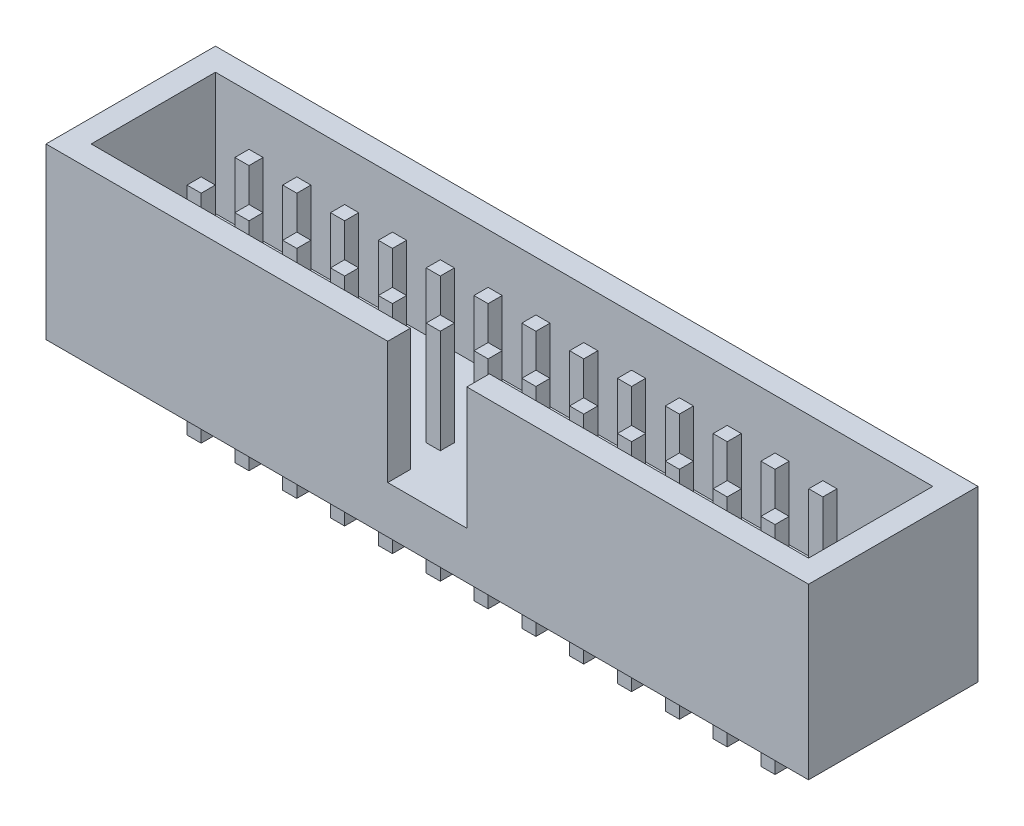
SolidWorks part; units mm, degrees
ref_plane "前视基准面" through (0, 0, 0) normal (0, 0, 1) x (1, 0, 0)
ref_plane "上视基准面" through (0, 0, 0) normal (0, 1, 0) x (1, 0, 0)
ref_plane "右视基准面" through (0, 0, 0) normal (1, 0, 0) x (0, 0, -1)
sketch "草图1" plane through (0, 0, 0) normal (0, 1, 0) x (1, 0, 0)
  line L0 (0, 85.0964) -> (0, -118.2031) construction
  line L1 (-20.25, 4.5) -> (20.25, 4.5)
  line L2 (-20.25, 4.5) -> (-20.25, -4.5)
  line L3 (-20.25, -4.5) -> (20.25, -4.5)
  line L4 (20.25, 4.5) -> (20.25, -4.5)
  line L5 (-200.5452, 0) -> (261.2352, 0) construction
  dimension "D1" = 9
  dimension "D2" = 40.5
extrude "拉伸1" add sketch "草图1" along normal blind 9
sketch "草图2" plane through (0, 9, 0) normal (0, 1, 0) x (-1, 0, 0)
  line L8 (-19.05, 3.3) -> (-19.05, -3.3)
  line L9 (19.05, 3.3) -> (-19.05, 3.3)
  line L10 (19.05, -3.3) -> (19.05, 3.3)
  line L11 (-19.05, -3.3) -> (19.05, -3.3)
  line L12 (-19.05, 3.3) -> (-19.05, -3.3)
  line L13 (19.05, 3.3) -> (-19.05, 3.3)
  line L14 (19.05, -3.3) -> (19.05, 3.3)
  line L15 (-19.05, -3.3) -> (19.05, -3.3)
  dimension "D1" = 1.2
extrude "切除-拉伸1" cut sketch "草图2" against normal blind 6.5
sketch "草图3" plane through (0, 0, 4.5) normal (0, 0, 1) x (1, 0, 0)
  line L0 (-20.25, 9) -> (20.25, 9) construction
  line L1 (-2.1, 9) -> (2.1, 9)
  line L2 (-2.1, 9) -> (-2.1, 2.5)
  line L3 (-2.1, 2.5) -> (2.1, 2.5)
  line L4 (2.1, 9) -> (2.1, 2.5)
  line L5 (-19.05, 2.5) -> (19.05, 2.5) construction
  line L6 (0, 9.4226) -> (0, -4.0288) construction
  dimension "D1" = 4.2
extrude "切除-拉伸2" cut sketch "草图3" against normal blind 6.5
sketch "草图5" plane through (0, 0, 0) normal (0, -1, 0) x (1, 0, 0)
  line L0 (0, 6.0683) -> (0, -6.9786) construction
  line L1 (-21.1981, 0) -> (21.4095, 0) construction
  line L2 (-2.4898, 1.27) -> (1.0953, 1.27) construction
  line L3 (-0.375, 0.895) -> (0.375, 0.895)
  line L4 (-0.375, 0.895) -> (-0.375, 1.645)
  line L5 (-0.375, 1.645) -> (0.375, 1.645)
  line L6 (0.375, 0.895) -> (0.375, 1.645)
  line L7 (2.165, 0.895) -> (2.915, 0.895)
  line L8 (2.165, 0.895) -> (2.165, 1.645)
  line L9 (2.165, 1.645) -> (2.915, 1.645)
  line L10 (2.915, 0.895) -> (2.915, 1.645)
  line L11 (4.705, 0.895) -> (5.455, 0.895)
  line L12 (4.705, 0.895) -> (4.705, 1.645)
  line L13 (4.705, 1.645) -> (5.455, 1.645)
  line L14 (5.455, 0.895) -> (5.455, 1.645)
  line L15 (7.245, 0.895) -> (7.995, 0.895)
  line L16 (7.245, 0.895) -> (7.245, 1.645)
  line L17 (7.245, 1.645) -> (7.995, 1.645)
  line L18 (7.995, 0.895) -> (7.995, 1.645)
  line L19 (9.785, 0.895) -> (10.535, 0.895)
  line L20 (9.785, 0.895) -> (9.785, 1.645)
  line L21 (9.785, 1.645) -> (10.535, 1.645)
  line L22 (10.535, 0.895) -> (10.535, 1.645)
  line L23 (12.325, 0.895) -> (13.075, 0.895)
  line L24 (12.325, 0.895) -> (12.325, 1.645)
  line L25 (12.325, 1.645) -> (13.075, 1.645)
  line L26 (13.075, 0.895) -> (13.075, 1.645)
  line L27 (14.865, 0.895) -> (15.615, 0.895)
  line L28 (14.865, 0.895) -> (14.865, 1.645)
  line L29 (14.865, 1.645) -> (15.615, 1.645)
  line L30 (15.615, 0.895) -> (15.615, 1.645)
  line L31 (-2.915, 0.895) -> (-2.165, 0.895)
  line L32 (-2.915, 0.895) -> (-2.915, 1.645)
  line L33 (-2.915, 1.645) -> (-2.165, 1.645)
  line L34 (-2.165, 0.895) -> (-2.165, 1.645)
  line L35 (-5.455, 0.895) -> (-4.705, 0.895)
  line L36 (-5.455, 0.895) -> (-5.455, 1.645)
  line L37 (-5.455, 1.645) -> (-4.705, 1.645)
  line L38 (-4.705, 0.895) -> (-4.705, 1.645)
  line L39 (-7.995, 0.895) -> (-7.245, 0.895)
  line L40 (-7.995, 0.895) -> (-7.995, 1.645)
  line L41 (-7.995, 1.645) -> (-7.245, 1.645)
  line L42 (-7.245, 0.895) -> (-7.245, 1.645)
  line L43 (-10.535, 0.895) -> (-9.785, 0.895)
  line L44 (-10.535, 0.895) -> (-10.535, 1.645)
  line L45 (-10.535, 1.645) -> (-9.785, 1.645)
  line L46 (-9.785, 0.895) -> (-9.785, 1.645)
  line L47 (-13.075, 0.895) -> (-12.325, 0.895)
  line L48 (-13.075, 0.895) -> (-13.075, 1.645)
  line L49 (-13.075, 1.645) -> (-12.325, 1.645)
  line L50 (-12.325, 0.895) -> (-12.325, 1.645)
  line L51 (-15.615, 0.895) -> (-14.865, 0.895)
  line L52 (-15.615, 0.895) -> (-15.615, 1.645)
  line L53 (-15.615, 1.645) -> (-14.865, 1.645)
  line L54 (-14.865, 0.895) -> (-14.865, 1.645)
  line L55 (-2.4898, -1.27) -> (1.0953, -1.27) construction
  line L56 (-14.865, -0.895) -> (-14.865, -1.645)
  line L57 (-15.615, -1.645) -> (-14.865, -1.645)
  line L58 (-15.615, -0.895) -> (-15.615, -1.645)
  line L59 (-15.615, -0.895) -> (-14.865, -0.895)
  line L60 (-12.325, -0.895) -> (-12.325, -1.645)
  line L61 (-13.075, -1.645) -> (-12.325, -1.645)
  line L62 (-13.075, -0.895) -> (-13.075, -1.645)
  line L63 (-13.075, -0.895) -> (-12.325, -0.895)
  line L64 (-9.785, -0.895) -> (-9.785, -1.645)
  line L65 (-10.535, -1.645) -> (-9.785, -1.645)
  line L66 (-10.535, -0.895) -> (-10.535, -1.645)
  line L67 (-10.535, -0.895) -> (-9.785, -0.895)
  line L68 (-7.245, -0.895) -> (-7.245, -1.645)
  line L69 (-7.995, -1.645) -> (-7.245, -1.645)
  line L70 (-7.995, -0.895) -> (-7.995, -1.645)
  line L71 (-7.995, -0.895) -> (-7.245, -0.895)
  line L72 (-4.705, -0.895) -> (-4.705, -1.645)
  line L73 (-5.455, -1.645) -> (-4.705, -1.645)
  line L74 (-5.455, -0.895) -> (-5.455, -1.645)
  line L75 (-5.455, -0.895) -> (-4.705, -0.895)
  line L76 (-2.165, -0.895) -> (-2.165, -1.645)
  line L77 (-2.915, -1.645) -> (-2.165, -1.645)
  line L78 (-2.915, -0.895) -> (-2.915, -1.645)
  line L79 (-2.915, -0.895) -> (-2.165, -0.895)
  line L80 (15.615, -0.895) -> (15.615, -1.645)
  line L81 (14.865, -1.645) -> (15.615, -1.645)
  line L82 (14.865, -0.895) -> (14.865, -1.645)
  line L83 (14.865, -0.895) -> (15.615, -0.895)
  line L84 (13.075, -0.895) -> (13.075, -1.645)
  line L85 (12.325, -1.645) -> (13.075, -1.645)
  line L86 (12.325, -0.895) -> (12.325, -1.645)
  line L87 (12.325, -0.895) -> (13.075, -0.895)
  line L88 (10.535, -0.895) -> (10.535, -1.645)
  line L89 (9.785, -1.645) -> (10.535, -1.645)
  line L90 (9.785, -0.895) -> (9.785, -1.645)
  line L91 (9.785, -0.895) -> (10.535, -0.895)
  line L92 (7.995, -0.895) -> (7.995, -1.645)
  line L93 (7.245, -1.645) -> (7.995, -1.645)
  line L94 (7.245, -0.895) -> (7.245, -1.645)
  line L95 (7.245, -0.895) -> (7.995, -0.895)
  line L96 (5.455, -0.895) -> (5.455, -1.645)
  line L97 (4.705, -1.645) -> (5.455, -1.645)
  line L98 (4.705, -0.895) -> (4.705, -1.645)
  line L99 (4.705, -0.895) -> (5.455, -0.895)
  line L100 (2.915, -0.895) -> (2.915, -1.645)
  line L101 (2.165, -1.645) -> (2.915, -1.645)
  line L102 (2.165, -0.895) -> (2.165, -1.645)
  line L103 (2.165, -0.895) -> (2.915, -0.895)
  line L104 (0.375, -0.895) -> (0.375, -1.645)
  line L105 (-0.375, -1.645) -> (0.375, -1.645)
  line L106 (-0.375, -0.895) -> (-0.375, -1.645)
  line L107 (-0.375, -0.895) -> (0.375, -0.895)
  dimension "D1" = 0.75
  dimension "D2" = 0.75
  dimension "D3" = 1.27
extrude "拉伸2" add sketch "草图5" along normal blind 3.5 and the other way offset from surface (8 mm away) 1 other way up to face at (0, 9, 1.3)
